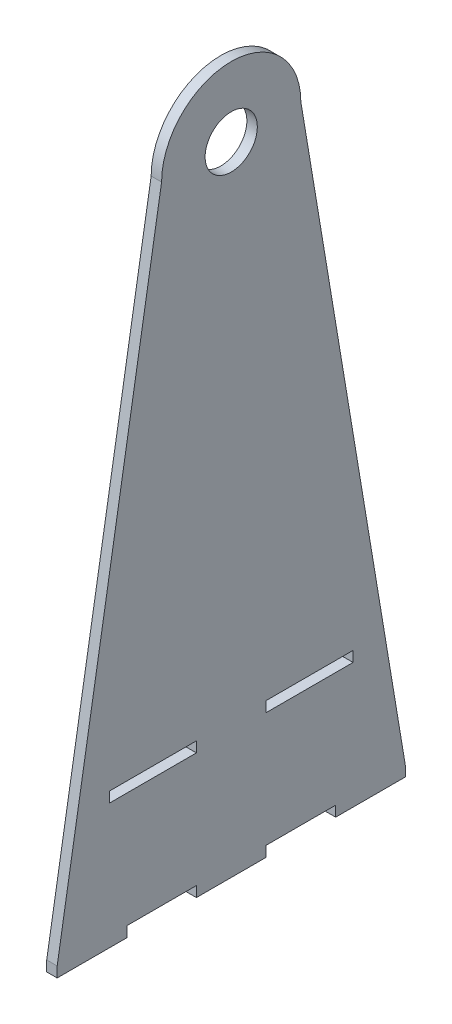
SolidWorks part; units mm, degrees
ref_plane "Alzado" through (0, 0, 0) normal (0, 0, 1) x (1, 0, 0)
ref_plane "Planta" through (0, 0, 0) normal (0, 1, 0) x (1, 0, 0)
ref_plane "Vista lateral" through (0, 0, 0) normal (1, 0, 0) x (0, 0, -1)
sketch "Sketch2" plane through (0, 0, 0) normal (1, 0, 0) x (0, 0, -1)
  line L0 (0, 0) -> (50, 0) construction
  line L1 (50, 0) -> (-50, 0)
  line L2 (0, 0) -> (0, 160) construction
  line L3 (-50, 0) -> (-20, 180)
  line L4 (50, 0) -> (20, 180)
  line L5 (0, 172.5) -> (0, 180) construction
  arc A0 (20, 180) -> (-20, 180) centre (0, 180) ccw
  circle A1 centre (0, 180) radius 7.5
  dimension "D1" = 50
  dimension "D2" = 100
  dimension "D3" = 180
extrude "Boss-Extrude1" add sketch "Sketch2" along normal mid plane 3
sketch "Sketch3" plane through (-1.5, 0, 0) normal (-1, 0, 0) x (0, 0, 1)
  line L0 (0, 0) -> (0, 33) construction
  line L4 (35, 36) -> (35, 33)
  line L5 (10, 33) -> (35, 33)
  line L8 (-10, 36) -> (-35, 36)
  line L9 (10, 36) -> (10, 33)
  line L10 (10, 36) -> (35, 36)
  line L11 (-10, 36) -> (-10, 33)
  line L12 (-10, 33) -> (-35, 33)
  line L13 (-35, 36) -> (-35, 33)
  dimension "D1" = 33
  dimension "D2" = 3
extrude "Cut-Extrude1" cut sketch "Sketch3" against normal blind 4
sketch "Sketch4" plane through (0, 0, 0) normal (0, -1, 0) x (1, 0, 0)
  line L0 (1.5, 50) -> (-1.5, 50)
  line L1 (-1.5, 50) -> (-1.5, 30)
  line L2 (-1.5, 30) -> (1.5, 30)
  line L3 (1.5, 30) -> (1.5, 50)
  line L4 (-1.5, 10) -> (-1.5, -10)
  line L5 (-1.5, -10) -> (1.5, -10)
  line L6 (1.5, -10) -> (1.5, 10)
  line L7 (1.5, 10) -> (-1.5, 10)
  line L8 (-1.5, -50) -> (1.5, -50)
  line L9 (1.5, -50) -> (1.5, -30)
  line L10 (1.5, -30) -> (-1.5, -30)
  line L11 (-1.5, -30) -> (-1.5, -50)
  point P14 (0, 0)
  point P17 (0, 0)
  point P18 (0, 0)
  point P19 (0, 0)
  line M6 (-1.5, 50) -> (-1.5, -50)
  line M7 (-1.5, -50) -> (1.5, -50)
  line M8 (1.5, -50) -> (1.5, 50)
  dimension "D1" = 20
  dimension "D2" = 20
  dimension "D3" = 20
  dimension "D4" = 20
extrude "Boss-Extrude2" add sketch "Sketch4" along normal blind 3 contours L7 L5 M8 M6 | L10 M8 M6 M7 | L1 L2 L3 L0
